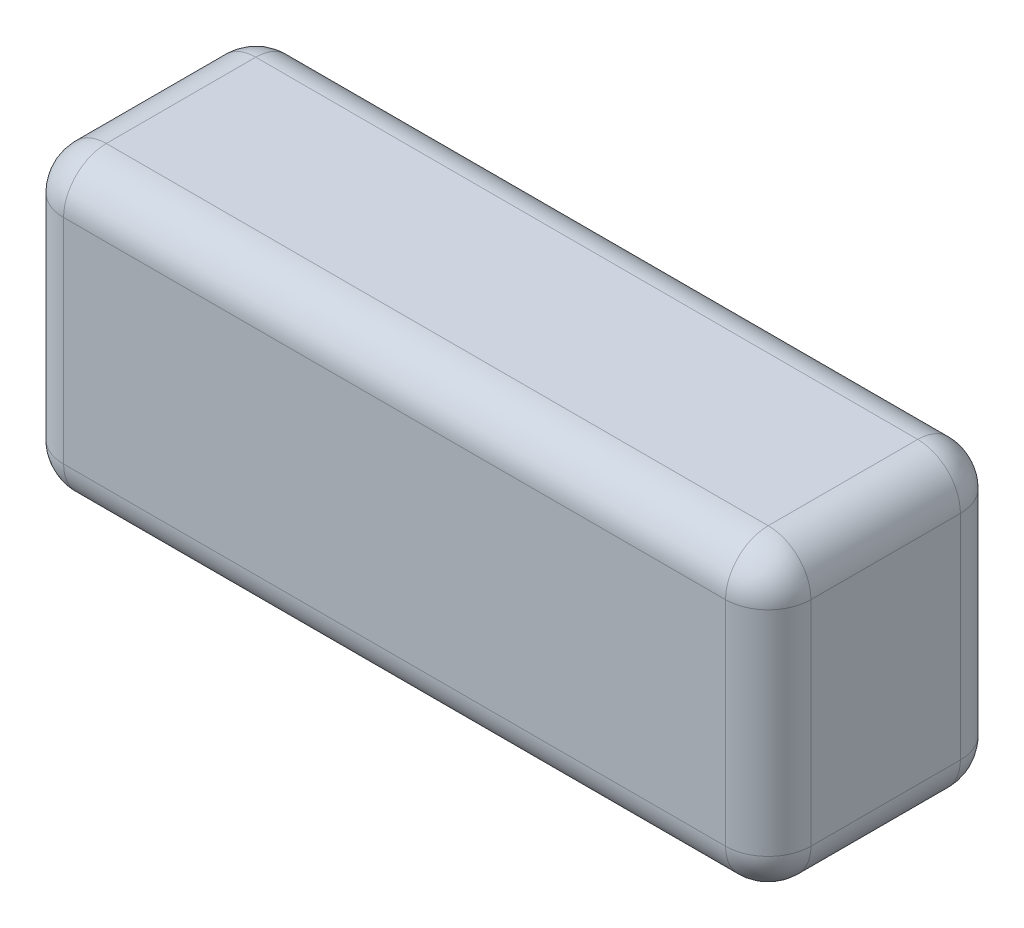
SolidWorks part; units mm, degrees
ref_plane "Front Plane" through (0, 0, 0) normal (0, 0, 1) x (1, 0, 0)
ref_plane "Top Plane" through (0, 0, 0) normal (0, 1, 0) x (1, 0, 0)
ref_plane "Right Plane" through (0, 0, 0) normal (1, 0, 0) x (0, 0, -1)
sketch "Sketch1" plane through (0, 0, 0) normal (0, 1, 0) x (1, 0, 0)
  line L1 (-70, 22) -> (70, 22)
  line L2 (-70, 22) -> (-70, -22)
  line L3 (-70, -22) -> (70, -22)
  line L4 (70, 22) -> (70, -22)
  line L5 (-70, 22) -> (70, -22) construction
  line L6 (-70, -22) -> (70, 22) construction
  point P0 (0, 0)
  dimension "D1" = 140
  dimension "D2" = 44
extrude "Boss-Extrude1" add sketch "Sketch1" along normal blind 56
fillet "Fillet1" radius 8 12 edges at (0, 56, 22) (0, 0, 22) (0, 56, -22) (0, 0, -22) (-70, 28, -22) (-70, 56, 0) (-70, 28, 22) (-70, 0, 0) (70, 28, 22) (70, 56, 0) (70, 28, -22) (70, 0, 0)
sketch "Sketch2" plane through (0, 0, -22) normal (0, 0, -1) x (-1, 0, 0)
  line L0 (-62, 48) -> (62, 8) construction
  line L1 (-62, 8) -> (62, 48) construction
  circle A0 centre (0, 28) radius 0.9077
extrude "Boss-Extrude2" add sketch "Sketch2" along normal blind 1
